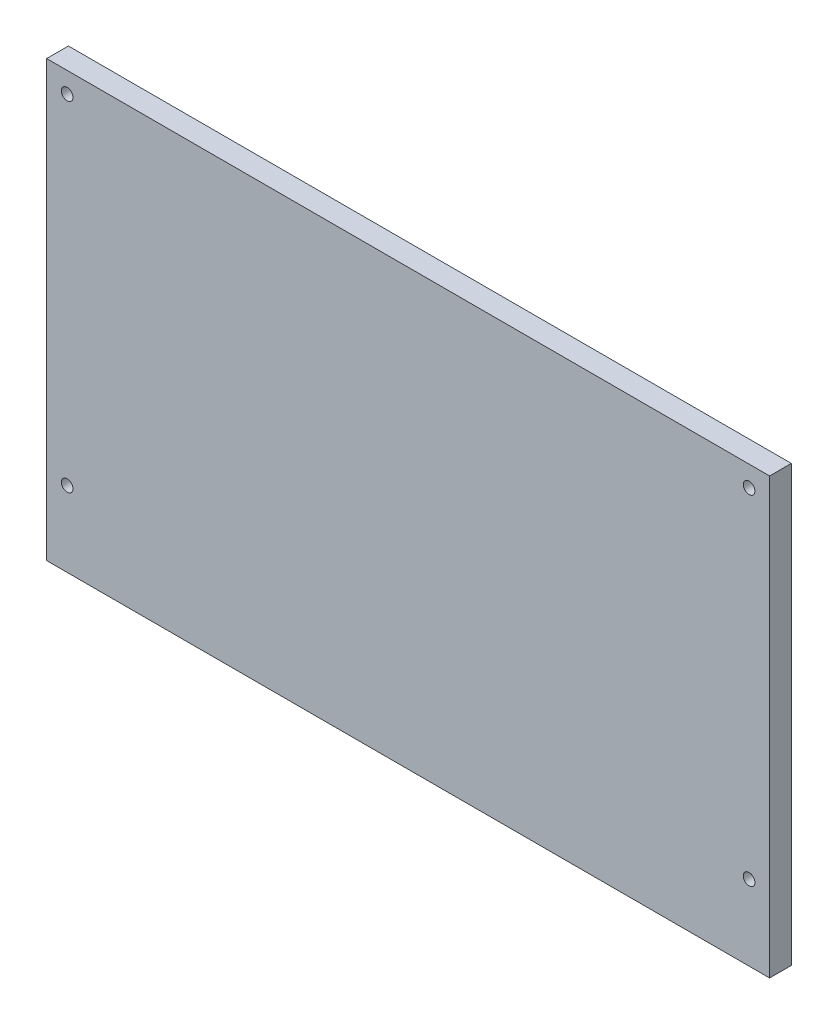
SolidWorks part; units mm, degrees
material "Acrylic (Medium-high impact)"
ref_plane "Front Plane" through (0, 0, 0) normal (0, 0, 1) x (1, 0, 0)
ref_plane "Top Plane" through (0, 0, 0) normal (0, 1, 0) x (1, 0, 0)
ref_plane "Right Plane" through (0, 0, 0) normal (1, 0, 0) x (0, 0, -1)
sketch "Sketch1" plane through (0, 0, 0) normal (0, 0, 1) x (1, 0, 0)
  line L1 (211.1756, 127) -> (0, 127)
  line L2 (211.1756, 127) -> (211.1756, 0)
  line L3 (211.1756, 0) -> (0, 0)
  line L4 (0, 127) -> (0, 0)
  line L5 (211.1756, 127) -> (0, 0) construction
  line L6 (211.1756, 0) -> (0, 127) construction
  point P0 (105.5878, 63.5)
  dimension "D1" = 127
  dimension "D2" = 211.1756
extrude "Boss-Extrude1" add sketch "Sketch1" along normal blind 6.35
hole_wizard "M3 Clearance Hole1" positions "Sketch2" profile "Sketch3" hole size "M3" standard "ANSI Metric" end condition through all
sketch "Sketch2" plane through (0, 0, 6.35) normal (0, 0, 1) x (1, 0, 0)
  line L0 (0, 127) -> (0, 0) construction
  line L1 (211.1756, 127) -> (0, 127) construction
  line L2 (211.1756, 0) -> (211.1756, 127) construction
  line L3 (0, 0) -> (211.1756, 0) construction
  point P0 (5.9944, 121.0056)
  point P2 (5.9944, 21.9964)
  point P4 (205.1812, 21.9964)
  point P6 (205.1812, 121.0056)
  dimension "D1" = 5.9944
  dimension "D2" = 5.9944
  dimension "D3" = 5.9944
  dimension "D4" = 21.9964
sketch "Sketch3" plane through (5.9944, 121.0056, 6.35) normal (1, 0, 0) x (0, -1, 0)
  line L0 (0, 0) -> (0, 6.35)
  line L1 (0, 6.35) -> (1.7, 6.35)
  line L2 (1.7, 6.35) -> (1.7, 0)
  line L5 (1.7, 0) -> (0, 0)
  line L11 (0, -6.35) -> (0, 107.95) construction
  dimension "Thru Hole Dia." = 3.4
  dimension "Thru Hole Depth" = 6.35
sketch "Sketch4" plane through (0, 0, 6.35) normal (0, 0, 1) x (1, 0, 0)
  line L0 (0, 127) -> (0, 0) construction
  line L1 (46.99, 107.95) -> (50.4952, 107.95)
  line L2 (46.99, 107.95) -> (46.99, 44.45)
  line L3 (46.99, 44.45) -> (50.4952, 44.45)
  line L4 (50.4952, 107.95) -> (50.4952, 44.45)
  line L5 (160.6804, 107.95) -> (164.1856, 107.95)
  line L6 (160.6804, 107.95) -> (160.6804, 44.45)
  line L7 (160.6804, 44.45) -> (164.1856, 44.45)
  line L8 (164.1856, 107.95) -> (164.1856, 44.45)
  line L9 (211.1756, 0) -> (211.1756, 127) construction
  line L10 (211.1756, 127) -> (0, 127) construction
  dimension "D1" = 3.5052
  dimension "D2" = 63.5
  dimension "D3" = 46.99
  dimension "D4" = 46.99
  dimension "D5" = 19.05
extrude "Cut-Extrude1" [suppressed] cut sketch "Sketch4" against normal through all
sketch "Sketch5" plane through (0, 0, 6.35) normal (0, 0, 1) x (1, 0, 0)
  line L0 (0, 10.7092) -> (76.2, 0)
  line L1 (0, 127) -> (0, 0) construction
  line L2 (0, 0) -> (211.1756, 0) construction
  line L3 (76.2, 0) -> (0, 0)
  line L4 (0, 0) -> (0, 10.7092)
  line L5 (134.9756, 0) -> (211.1756, 0)
  line L6 (211.1756, 0) -> (211.1756, 10.7092)
  line L7 (211.1756, 0) -> (211.1756, 127) construction
  line L8 (211.1756, 10.7092) -> (134.9756, 0)
  dimension "D1" = 8
  dimension "D2" = 8
  dimension "D3" = 76.2
  dimension "D4" = 76.2
extrude "Cut-Extrude2" [suppressed] cut sketch "Sketch5" against normal through all
